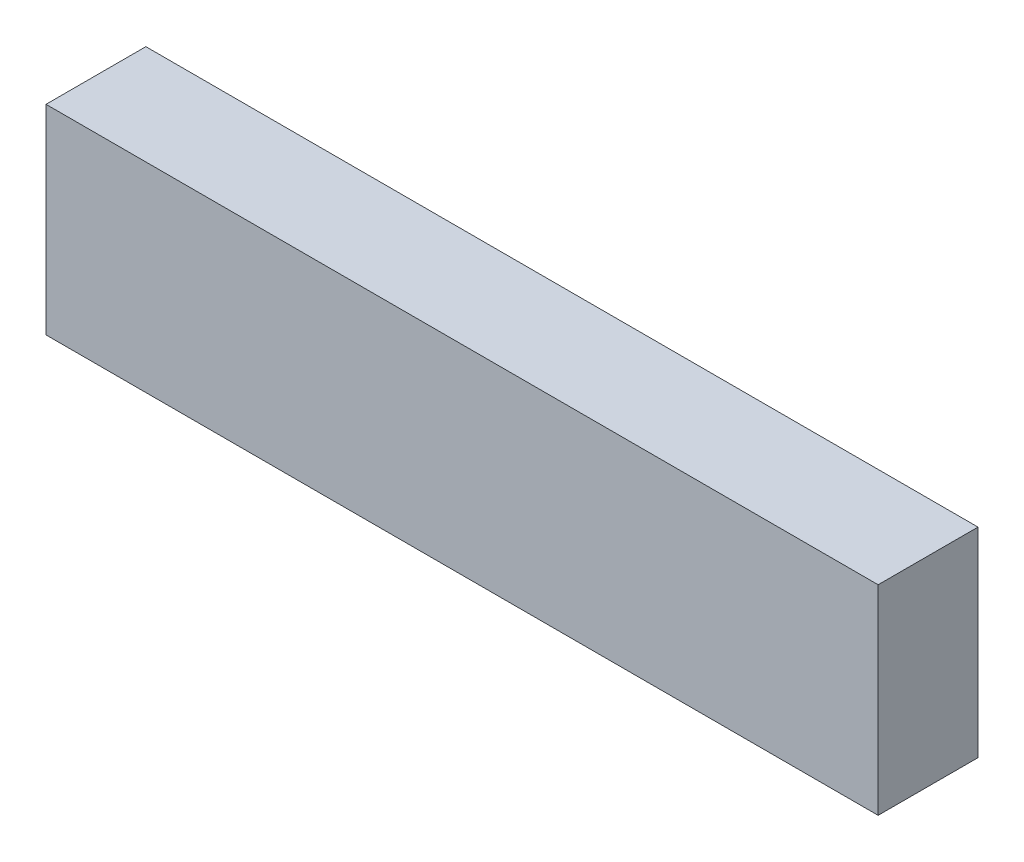
SolidWorks part; units mm, degrees
ref_plane "Plano frontal" through (0, 0, 0) normal (0, 0, 1) x (1, 0, 0)
ref_plane "Plano superior" through (0, 0, 0) normal (0, 1, 0) x (1, 0, 0)
ref_plane "Plano direito" through (0, 0, 0) normal (1, 0, 0) x (0, 0, -1)
sketch "Esboço1" plane through (0, 0, 0) normal (0, 0, 1) x (1, 0, 0)
  line L1 (-62.5, 15) -> (62.5, 15)
  line L2 (-62.5, 15) -> (-62.5, -15)
  line L3 (-62.5, -15) -> (62.5, -15)
  line L4 (62.5, 15) -> (62.5, -15)
  line L5 (-62.5, 15) -> (62.5, -15) construction
  line L6 (-62.5, -15) -> (62.5, 15) construction
  point P0 (0, 0)
  dimension "D1" = 125
  dimension "D2" = 30
extrude "Ressalto-extrusão1" add sketch "Esboço1" along normal blind 15
